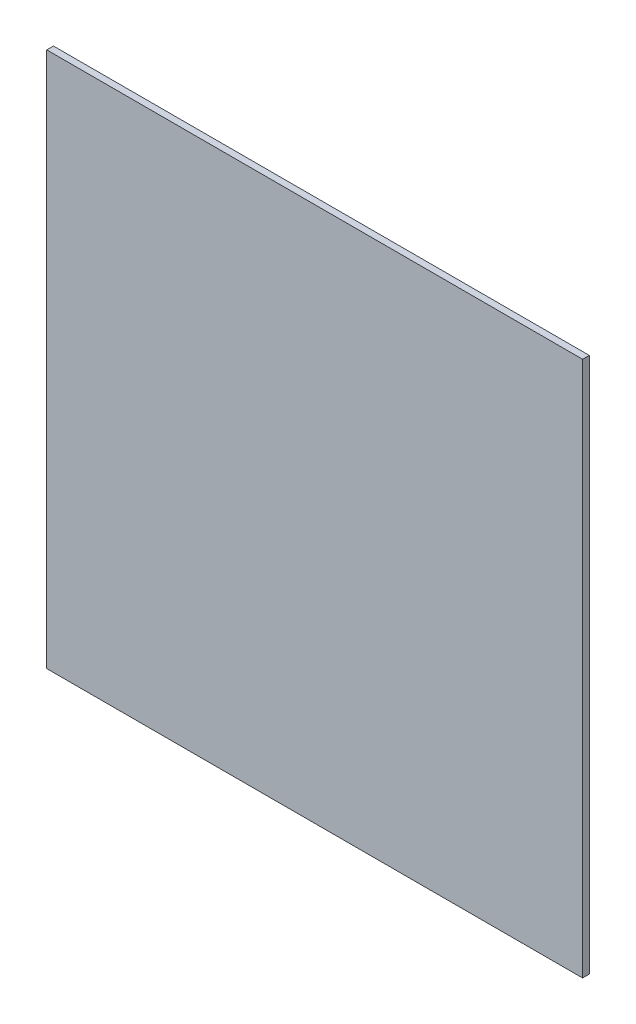
SolidWorks part; units mm, degrees
ref_plane "Front Plane" through (0, 0, 0) normal (0, 0, 1) x (1, 0, 0)
ref_plane "Top Plane" through (0, 0, 0) normal (0, 1, 0) x (1, 0, 0)
ref_plane "Right Plane" through (0, 0, 0) normal (1, 0, 0) x (0, 0, -1)
sketch "Sketch1" plane through (0, 0, 0) normal (0, 0, 1) x (1, 0, 0)
  line L1 (303.911, -24.5109) -> (430.911, -24.5109)
  line L2 (303.911, -24.5109) -> (303.911, -151.5109)
  line L3 (303.911, -151.5109) -> (430.911, -151.5109)
  line L4 (430.911, -24.5109) -> (430.911, -151.5109)
  line L5 (303.911, -24.5109) -> (430.911, -151.5109) construction
  line L6 (303.911, -151.5109) -> (430.911, -24.5109) construction
  point P0 (367.411, -88.0109)
  dimension "D1" = 127
  dimension "D2" = 127
extrude "Boss-Extrude1" add sketch "Sketch1" against normal blind 1.5875
